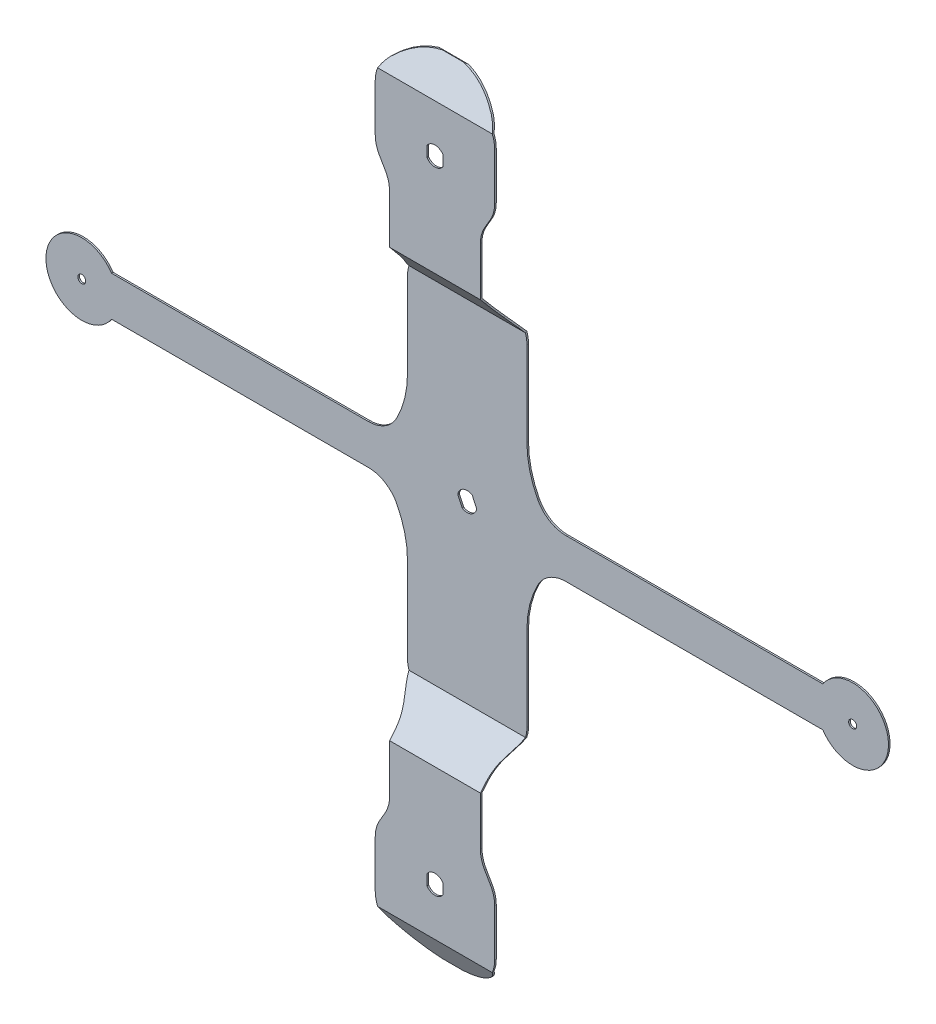
SolidWorks part; units mm, degrees
ref_plane "Alzado" through (0, 0, 0) normal (0, 0, 1) x (1, 0, 0)
ref_plane "Planta" through (0, 0, 0) normal (0, 1, 0) x (1, 0, 0)
ref_plane "Vista lateral" through (0, 0, 0) normal (1, 0, 0) x (0, 0, -1)
sketch "Croquis1" plane through (0, 0, 0) normal (1, 0, 0) x (0, 0, -1)
  line L0 (-36.5, -110) -> (-36.5, 110)
  line L1 (-36.5, 110) -> (-56.7478, 134.1304)
  line L2 (0, 0) -> (-82.8072, 0) construction
  line L3 (-56.7478, 134.1304) -> (-56.7478, 198)
  line L4 (-36.5, -110) -> (-56.7478, -134.1304)
  line L5 (-56.7478, -134.1304) -> (-56.7478, -198)
  line L13 (-56.7478, -198) -> (-56.7478, -228)
  line L14 (-56.7478, -228) -> (-45.7478, -247.0526)
  line L15 (-56.7478, 228) -> (-45.7478, 247.0526)
  line L16 (-56.7478, 198) -> (-56.7478, 228)
  line L17 (-55.7478, 198) -> (-55.7478, 227.7321)
  line L18 (-55.7478, 227.7321) -> (-44.8818, 246.5526)
  line L19 (-55.7478, -227.7321) -> (-44.8818, -246.5526)
  line L20 (-55.7478, -198) -> (-55.7478, -227.7321)
  line L21 (-55.7478, -134.4944) -> (-55.7478, -198)
  line L22 (-35.5, -110.364) -> (-55.7478, -134.4944)
  line L23 (-35.5, -110.364) -> (-35.5, 110.364)
  line L24 (-35.5, 110.364) -> (-55.7478, 134.4944)
  line L25 (-55.7478, 134.4944) -> (-55.7478, 198)
  line L26 (-45.7478, -247.0526) -> (-44.8818, -246.5526)
  line L27 (-45.7478, 247.0526) -> (-44.8818, 246.5526)
  point P9 (-36.5, 0)
  dimension "D1" = 36.5
  dimension "D2" = 50
  dimension "D3" = 31.5
  dimension "D4" = 110
  dimension "D5" = 396
  dimension "D7" = 30
  dimension "D8" = 22
  dimension "D9" = 60
  dimension "D6" = 1
extrude "Saliente-Extruir1" add sketch "Croquis1" along normal mid plane 542
sketch "Croquis2" plane through (0, 0, 0) normal (0, 0, 1) x (1, 0, 0)
  line L1 (0, 277.0309) -> (0, -277.0309) construction
  line L7 (-31.1795, 174.5741) -> (-34.8205, 180.8806)
  line L9 (-300.4496, 0) -> (300.4496, 0) construction
  line L10 (-223.2917, 12.5) -> (-61.998, 12.5)
  line L11 (-223.2917, -12.5) -> (-61.998, -12.5)
  line L12 (-37.5, 50.7685) -> (-37.5, 103.9857)
  line L13 (-34.8205, 113.9857) -> (-31.1795, 120.2921)
  line L14 (-28.5, 130.2921) -> (-28.5, 164.5741)
  line L15 (-37.5, 190.8806) -> (-37.5, 220.3536)
  line L16 (37.5, 168.6253) -> (-37.5, 168.6253) construction
  line L17 (37.5, 168.6253) -> (37.5, 227.3747) construction
  line L18 (37.5, 227.3747) -> (-37.5, 227.3747) construction
  line L19 (-37.5, 168.6253) -> (-37.5, 227.3747) construction
  line L31 (37.5, 168.6253) -> (-37.5, 227.3747) construction
  line L33 (37.5, 227.3747) -> (-37.5, 168.6253) construction
  line L34 (-34.8205, -113.9857) -> (-31.1795, -120.2921)
  line L35 (-37.5, -50.7685) -> (-37.5, -103.9857)
  line L36 (-28.5, -130.2921) -> (-28.5, -164.5741)
  line L37 (-31.1795, -174.5741) -> (-34.8205, -180.8806)
  line L38 (-37.5, -190.8806) -> (-37.5, -220.3536)
  line L39 (37.5, -190.8806) -> (37.5, -220.3536)
  line L40 (31.1795, -174.5741) -> (34.8205, -180.8806)
  line L41 (28.5, -130.2921) -> (28.5, -164.5741)
  line L42 (37.5, -50.7685) -> (37.5, -103.9857)
  line L43 (34.8205, -113.9857) -> (31.1795, -120.2921)
  line L44 (37.5, 190.8806) -> (37.5, 220.3536)
  line L45 (28.5, 130.2921) -> (28.5, 164.5741)
  line L46 (34.8205, 113.9857) -> (31.1795, 120.2921)
  line L47 (37.5, 50.7685) -> (37.5, 103.9857)
  line L48 (223.2917, -12.5) -> (61.998, -12.5)
  line L49 (223.2917, 12.5) -> (61.998, 12.5)
  line L50 (31.1795, 174.5741) -> (34.8205, 180.8806)
  line L52 (-300.4496, 277.0309) -> (300.4496, 277.0309)
  line L53 (-300.4496, 277.0309) -> (-300.4496, -277.0309)
  line L54 (-300.4496, -277.0309) -> (300.4496, -277.0309)
  line L55 (300.4496, 277.0309) -> (300.4496, -277.0309)
  line L56 (-300.4496, 277.0309) -> (300.4496, -277.0309) construction
  line L57 (-300.4496, -277.0309) -> (300.4496, 277.0309) construction
  circle A9 centre (0, 0) radius 247.5 construction
  arc A10 (-223.2917, 12.5) -> (-223.2917, -12.5) centre (-242, 0) ccw
  circle A11 centre (0, 0) radius 50 construction
  arc A12 (-61.998, 12.5) -> (-44.2843, 23.2143) centre (-61.998, 32.5) ccw
  arc A13 (-61.998, -12.5) -> (-44.2843, -23.2143) centre (-61.998, -32.5) cw
  arc A14 (-37.5, 50.7685) -> (-44.2843, 23.2143) centre (-96.8474, 50.7685) cw
  circle A15 centre (0, 198) radius 40 construction
  arc A16 (31.5, 234.6364) -> (-31.5, 234.6364) centre (0, 202.5) ccw
  arc A17 (-31.5, 234.6364) -> (-37.5, 220.3536) centre (-17.5, 220.3536) ccw
  arc A18 (-34.8205, 180.8806) -> (-37.5, 190.8806) centre (-17.5, 190.8806) cw
  arc A19 (-28.5, 164.5741) -> (-31.1795, 174.5741) centre (-48.5, 164.5741) ccw
  arc A20 (-31.1795, 120.2921) -> (-28.5, 130.2921) centre (-48.5, 130.2921) ccw
  arc A21 (-37.5, 103.9857) -> (-34.8205, 113.9857) centre (-17.5, 103.9857) cw
  arc A22 (-37.5, -103.9857) -> (-34.8205, -113.9857) centre (-17.5, -103.9857) ccw
  arc A23 (-31.1795, -120.2921) -> (-28.5, -130.2921) centre (-48.5, -130.2921) cw
  arc A24 (-37.5, -50.7685) -> (-44.2843, -23.2143) centre (-96.8474, -50.7685) ccw
  arc A25 (-28.5, -164.5741) -> (-31.1795, -174.5741) centre (-48.5, -164.5741) cw
  arc A26 (-34.8205, -180.8806) -> (-37.5, -190.8806) centre (-17.5, -190.8806) ccw
  arc A27 (-31.5, -234.6364) -> (-37.5, -220.3536) centre (-17.5, -220.3536) cw
  arc A28 (31.5, -234.6364) -> (-31.5, -234.6364) centre (0, -202.5) cw
  arc A29 (31.5, -234.6364) -> (37.5, -220.3536) centre (17.5, -220.3536) ccw
  arc A30 (34.8205, -180.8806) -> (37.5, -190.8806) centre (17.5, -190.8806) cw
  arc A31 (28.5, -164.5741) -> (31.1795, -174.5741) centre (48.5, -164.5741) ccw
  arc A32 (37.5, -50.7685) -> (44.2843, -23.2143) centre (96.8474, -50.7685) cw
  arc A33 (31.1795, -120.2921) -> (28.5, -130.2921) centre (48.5, -130.2921) ccw
  arc A34 (37.5, -103.9857) -> (34.8205, -113.9857) centre (17.5, -103.9857) cw
  arc A35 (37.5, 103.9857) -> (34.8205, 113.9857) centre (17.5, 103.9857) ccw
  arc A36 (31.1795, 120.2921) -> (28.5, 130.2921) centre (48.5, 130.2921) cw
  arc A37 (28.5, 164.5741) -> (31.1795, 174.5741) centre (48.5, 164.5741) cw
  arc A38 (34.8205, 180.8806) -> (37.5, 190.8806) centre (17.5, 190.8806) ccw
  arc A39 (31.5, 234.6364) -> (37.5, 220.3536) centre (17.5, 220.3536) cw
  arc A40 (37.5, 50.7685) -> (44.2843, 23.2143) centre (96.8474, 50.7685) ccw
  arc A41 (61.998, -12.5) -> (44.2843, -23.2143) centre (61.998, -32.5) ccw
  arc A42 (61.998, 12.5) -> (44.2843, 23.2143) centre (61.998, 32.5) cw
  arc A43 (223.2917, 12.5) -> (223.2917, -12.5) centre (242, 0) cw
  point P6 (0, 0)
  point P7 (0, 0)
  point P38 (-37.5, 185.5216)
  point P41 (-28.5, 169.9331)
  point P44 (-28.5, 124.9331)
  point P48 (-37.5, 109.3447)
  point P108 (37.5, 109.3447)
  point P109 (28.5, 124.9331)
  point P110 (28.5, 169.9331)
  point P111 (37.5, 185.5216)
  dimension "D1" = 495
  dimension "D3" = 45
  dimension "D9" = 198
  dimension "D4" = 100
  dimension "D6" = 20
  dimension "D10" = 80
  dimension "D14" = 45
  dimension "D16" = 20
  dimension "D2" = 242
  dimension "D5" = 25
  dimension "D7" = 75
  dimension "D8" = 57
  dimension "D11" = 45
  dimension "D12" = 60
  dimension "D13" = 75
  dimension "D15" = 60
sketch "Croquis4" plane through (0, 0, 0) normal (0, 0, 1) x (1, 0, 0)
  line L0 (-326.6263, 0) -> (326.6263, 0) construction
  line L1 (0, 278.5393) -> (0, -278.5393) construction
  line L2 (-5, -194.6834) -> (5, -201.3166) construction
  line L3 (-5, 201.3166) -> (5, 201.3166) construction
  line L4 (-5, 201.3166) -> (-5, 194.6834)
  line L5 (-5, 194.6834) -> (5, 194.6834) construction
  line L6 (5, 201.3166) -> (5, 194.6834)
  line L7 (-5, 201.3166) -> (5, 194.6834) construction
  line L8 (-5, 194.6834) -> (5, 201.3166) construction
  line L9 (-5, -201.3166) -> (5, -194.6834) construction
  line L10 (-5, -194.6834) -> (5, -194.6834) construction
  line L11 (-5, -201.3166) -> (5, -201.3166) construction
  line L12 (5, -201.3166) -> (5, -194.6834)
  line L13 (-5, -201.3166) -> (-5, -194.6834)
  line L26 (-5.9332, 0.8928) -> (3.1299, 5.119) construction
  line L27 (-5.9332, 0.8928) -> (-3.1299, -5.119)
  line L28 (3.1299, 5.119) -> (5.9332, -0.8928)
  line L29 (-3.1299, -5.119) -> (5.9332, -0.8928) construction
  line L30 (0, 0) -> (-1.4017, 3.0059) construction
  arc A0 (-5, 194.6834) -> (5, 194.6834) centre (0, 198) ccw
  arc A1 (-3.1299, -5.119) -> (5.9332, -0.8928) centre (0, 0) ccw
  arc A4 (5, 201.3166) -> (-5, 201.3166) centre (0, 198) ccw
  arc A5 (5, -201.3166) -> (-5, -201.3166) centre (0, -198) cw
  arc A6 (-5, -194.6834) -> (5, -194.6834) centre (0, -198) cw
  circle A7 centre (-242, 0) radius 2.5
  arc A10 (3.1299, 5.119) -> (-5.9332, 0.8928) centre (0, 0) ccw
  circle A11 centre (242, 0) radius 2.5
  point P4 (0, 0)
  point P8 (0, 0)
  dimension "D3" = 5
  dimension "D4" = 10
  dimension "D5" = 12
  dimension "D6" = 12
  dimension "D1" = 198
  dimension "D2" = 242
  dimension "D8" = 10
  dimension "D9" = 25
extrude "Cortar-Extruir9" cut sketch "Croquis4" against normal through all both and the other way through all
extrude "Cortar-Extruir11" cut sketch "Croquis2" against normal through all both and the other way through all
